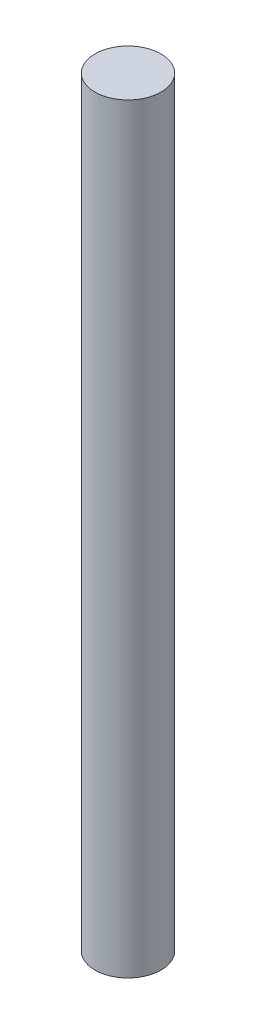
SolidWorks part; units mm, degrees
ref_plane "Alzado" through (0, 0, 0) normal (0, 0, 1) x (1, 0, 0)
ref_plane "Planta" through (0, 0, 0) normal (0, 1, 0) x (1, 0, 0)
ref_plane "Vista lateral" through (0, 0, 0) normal (1, 0, 0) x (0, 0, -1)
sketch "Croquis1" plane through (0, 0, 0) normal (0, 1, 0) x (1, 0, 0)
  circle A0 centre (0, 0) radius 4
  dimension "D1" = 8
extrude "Saliente-Extruir1" add sketch "Croquis1" along normal blind 92
